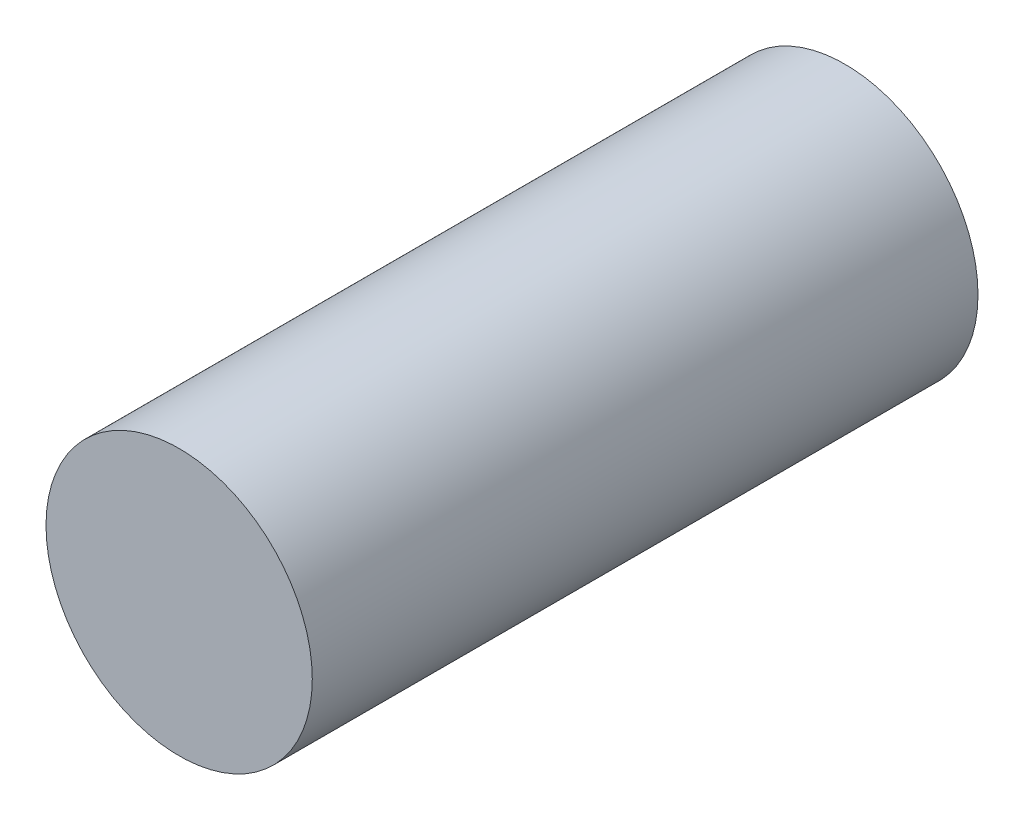
SolidWorks part; units mm, degrees
ref_plane "Front Plane" through (0, 0, 0) normal (0, 0, 1) x (1, 0, 0)
ref_plane "Top Plane" through (0, 0, 0) normal (0, 1, 0) x (1, 0, 0)
ref_plane "Right Plane" through (0, 0, 0) normal (1, 0, 0) x (0, 0, -1)
other "Configuration Table"
sketch "Sketch1" plane through (0, 0, 0) normal (0, 0, 1) x (1, 0, 0)
  circle A0 centre (300, 1334) radius 4
extrude "TOPPING_kat2_kapak_pimi_D8_1" add sketch "Sketch1" against normal blind 20 from offset 40 separate body
